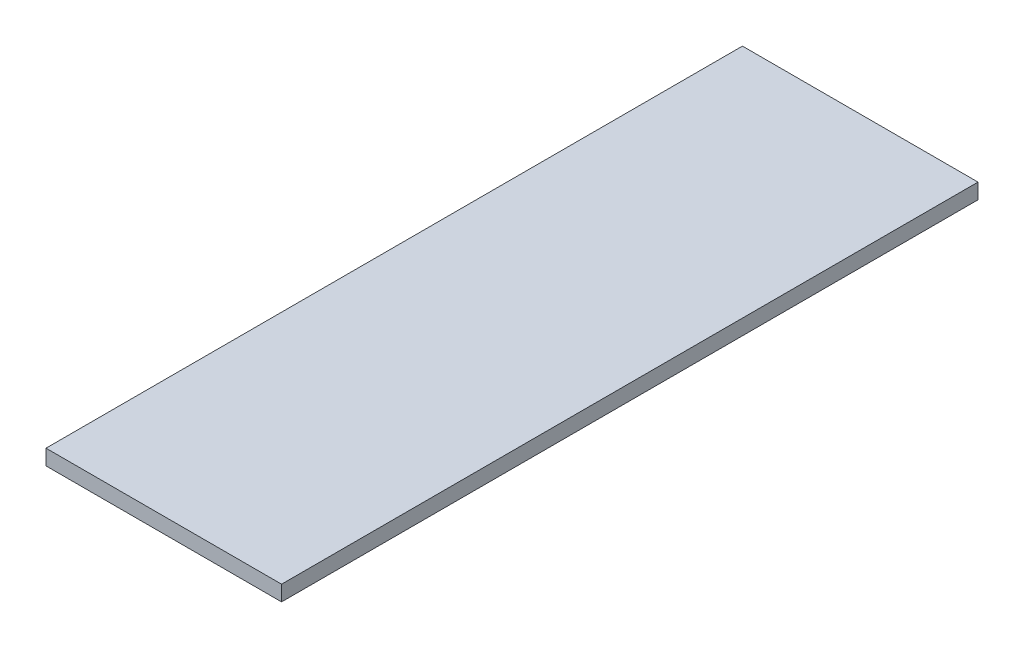
SolidWorks part; units mm, degrees
ref_plane "Front Plane" through (0, 0, 0) normal (0, 0, 1) x (1, 0, 0)
ref_plane "Top Plane" through (0, 0, 0) normal (0, 1, 0) x (1, 0, 0)
ref_plane "Right Plane" through (0, 0, 0) normal (1, 0, 0) x (0, 0, -1)
sketch "Sketch1" plane through (0, 0, 0) normal (0, 1, 0) x (1, 0, 0)
  line L1 (-61.9222, -6.4959) -> (-50.4222, -6.4959)
  line L2 (-61.9222, -6.4959) -> (-61.9222, -40.4959)
  line L3 (-61.9222, -40.4959) -> (-50.4222, -40.4959)
  line L4 (-50.4222, -6.4959) -> (-50.4222, -40.4959)
  dimension "D1" = 34
  dimension "D2" = 11.5
extrude "Boss-Extrude1" add sketch "Sketch1" along normal blind 0.75
scale "Scale1" scale about centroid uniform scaling yes scale factor 10
